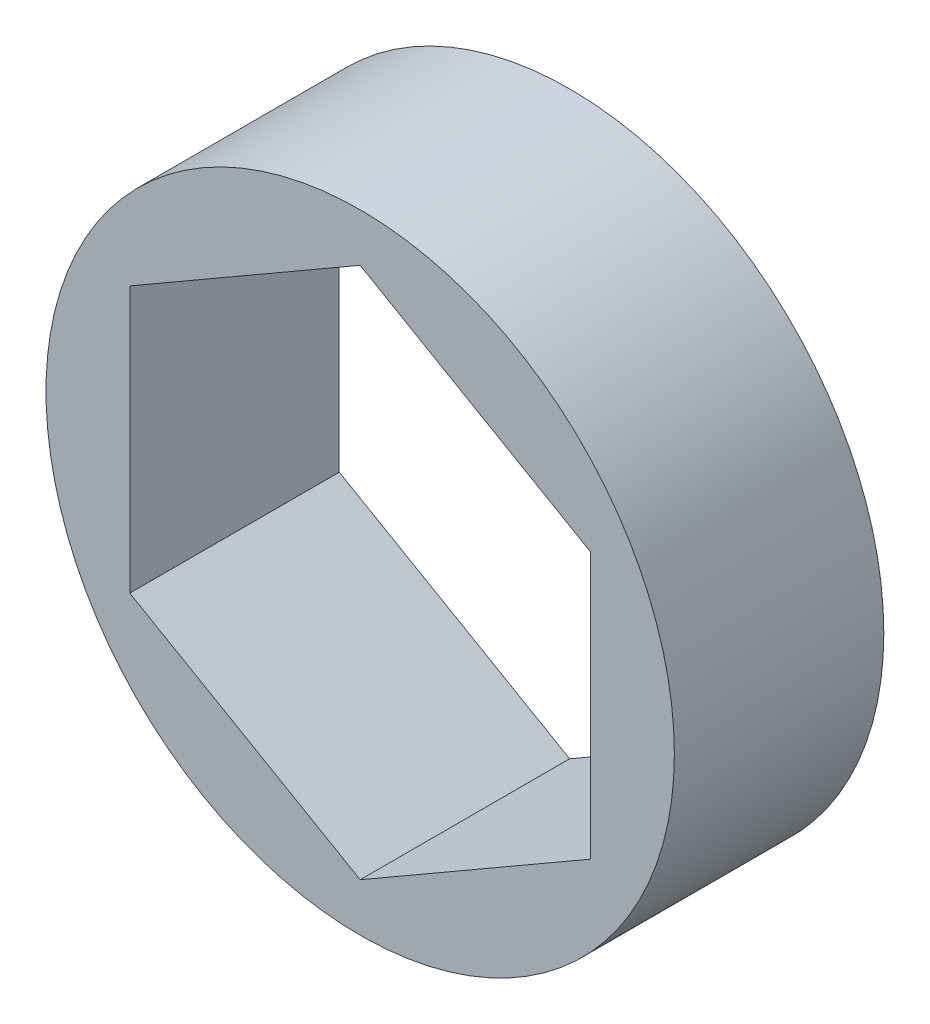
SolidWorks part; units mm, degrees
material "PET"
ref_plane "Front Plane" through (0, 0, 0) normal (0, 0, 1) x (1, 0, 0)
ref_plane "Top Plane" through (0, 0, 0) normal (0, 1, 0) x (1, 0, 0)
ref_plane "Right Plane" through (0, 0, 0) normal (1, 0, 0) x (0, 0, -1)
sketch "Sketch1" plane through (0, 0, 0) normal (0, 0, 1) x (1, 0, 0)
  line L1 (0, 8.0656) -> (-6.985, 4.0328)
  line L2 (-6.985, 4.0328) -> (-6.985, -4.0328)
  line L3 (-6.985, -4.0328) -> (0, -8.0656)
  line L4 (0, -8.0656) -> (6.985, -4.0328)
  line L5 (6.985, -4.0328) -> (6.985, 4.0328)
  line L6 (6.985, 4.0328) -> (0, 8.0656)
  circle A0 centre (0, 0) radius 6.985 construction
  circle A1 centre (0, 0) radius 9.525
  dimension "D1" = 13.97
  dimension "D2" = 19.05
extrude "Boss-Extrude1" add sketch "Sketch1" along normal mid plane 6.35
